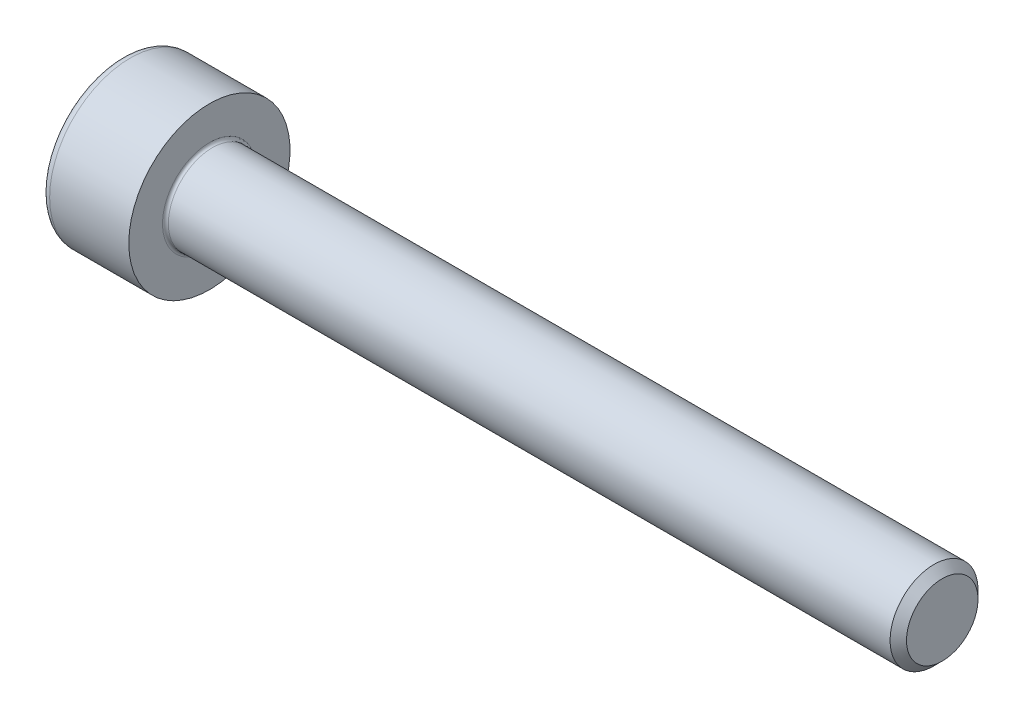
SolidWorks part; units mm, degrees
ref_plane "Plane1" through (0, 0, 0) normal (0, 0, 1) x (1, 0, 0)
ref_plane "Plane2" through (0, 0, 0) normal (0, 1, 0) x (1, 0, 0)
ref_plane "Plane3" through (0, 0, 0) normal (1, 0, 0) x (0, 0, -1)
sketch "BodySke" plane through (0, 0, 0) normal (0, 0, 1) x (1, 0, 0)
  line L0 (0, 0) -> (0, 2.75)
  line L1 (0, 2.75) -> (3, 2.75)
  line L2 (3, 2.75) -> (3, 1.5)
  line L3 (3, 1.5) -> (27.7195, 1.5)
  line L4 (28, 1.2195) -> (28, 0)
  line L5 (28, 0) -> (0, 0)
  line L6 (-31.75, 0) -> (127, 0) construction
  line L8 (28, 1.2195) -> (27.7195, 1.5)
  line L10 (28, -1.2195) -> (27.7195, -1.5) construction
  line L11 (3.5, 9.525) -> (3.5, 3.175) construction
  line L12 (10, 9.525) -> (10, 3.175) construction
  line L13 (-32, 9.525) -> (-32, 3.175) construction
  dimension "Diameter" = 3
  dimension "Head_ht" = 3
  dimension "Length" = 25
  dimension "Body_ch_ang" = 45
  dimension "Head_dia" = 5.5
  dimension "Minor_dia" = 2.439
  dimension "Advance" = 0.5
  dimension "Thread_nom" = 18
  dimension "Thread_length" = 60
revolve "Base-Revolve" add sketch "BodySke"
cosmetic thread "ThreadCosmetic" [suppressed]
fillet "Fillet1" radius 0.1 1 edges at (3, 0, 1.5)
fillet "Fillet2" radius 0.3 1 edges at (0, 0, 2.75)
sketch "Sketch2" plane through (0, 0, 0) normal (0, 0, 1) x (1, 0, 0)
  line L0 (0, 1.26) -> (1.3, 1.26)
  line L1 (1.3, 1.26) -> (2.0275, 0)
  line L2 (-31.75, 0) -> (127, 0) construction
  line L3 (2.0275, 0) -> (0, 0)
  line L4 (0, 0) -> (0, 1.26)
  line L6 (0, 0) -> (47.625, 0) construction
  dimension "D1" = 1.26
  dimension "D2" = 60
  dimension "Depth" = 1.3
revolve "Hex-PreBroach" cut sketch "Sketch2" angle 360 about L6
sketch "Sketch3" plane through (0, 0, 0) normal (-1, 0, 0) x (0, 0.5, 0.866)
  line L0 (0.7275, 1.26) -> (-0.7275, 1.26)
  line L1 (-0.7275, 1.26) -> (-1.4549, 0)
  line L2 (0.7275, 1.26) -> (1.4549, 0)
  line L3 (0.7275, -1.26) -> (1.4549, 0)
  line L4 (0.7275, -1.26) -> (-0.7275, -1.26)
  line L5 (-0.7275, -1.26) -> (-1.4549, 0)
  dimension "D1" = 1.26
  dimension "D2" = 1.26
  dimension "Hex_size" = 2.52
extrude "Hex" cut sketch "Sketch3" against normal blind 1.3
sketch "ThdSchSke" plane through (0, 0, 0) normal (0, 0, 1) x (1, 0, 0)
  line L0 (10, -1.2195) -> (9.8036, -1.5)
  line L1 (10, -1.2195) -> (10.1964, -1.5)
  line L2 (10.1964, -1.5) -> (10.1964, -1.875)
  line L3 (-3.175, 0) -> (5.1513, 0) construction
  line L4 (0, 2.45) -> (0, -2.45) construction
  line L5 (10.1964, -1.875) -> (9.8036, -1.875)
  line L6 (9.8036, -1.875) -> (9.8036, -1.5)
  dimension "Thread_minor" = 2.439
  dimension "Diameter" = 3
  dimension "Start" = 10
  dimension "SideAngle" = 55
  dimension "VeeAngle" = 70
  dimension "Overcut" = 3.75
revolve "ThreadSchematic" [suppressed] cut sketch "ThdSchSke" angle 360 about L3
pattern_linear "ThdSchPat" [suppressed]
equation "\"D2@Sketch3\" = \"Hex_size@Sketch3\" / 2"
equation "\"D1@Sketch3\" = \"Hex_size@Sketch3\" / 2"
equation "\"D1@Sketch2\" = \"Hex_size@Sketch3\" / 2"
equation "\"Thread_minor@ThreadCosmetic\"  =  \"Minor_dia@BodySke\""
equation "\"Depth@Sketch2\" =  \"Key_eng@Hex\""
equation "\"Thread_length@ThreadCosmetic\" = ((sgn( (\"Length@BodySke\" - \"Advance@BodySke\" * 3.0) - \"Thread_nom@BodySke\" )-1)*( (\"Length@BodySke\" - \"Advance@BodySke\" * 3.0) - \"Thread_nom@BodySke\" ))/-2+ \"Thread_nom@BodySke\""
equation "\"Thread_minor@ThdSchSke\" = \"Minor_dia@BodySke\""
equation "\"Diameter@ThdSchSke\" = \"Diameter@BodySke\""
equation "\"Overcut@ThdSchSke\" = \"Diameter@BodySke\" * 1.25"
equation "\"Start@ThdSchSke\" = \"Head_ht@BodySke\" + \"Length@BodySke\" - \"Thread_length@ThreadCosmetic\"  '---Non-countersunk---"
equation "\"Num_threads@ThdSchPat\" = int( \"Thread_length@ThreadCosmetic\" / \"Advance@BodySke\" + 0.999 )  + 1"
equation "\"Advance@ThdSchPat\" = \"Thread_length@ThreadCosmetic\" /  (\"Num_threads@ThdSchPat\" - 1) 'relax it"
equation "\"Num_threads@ThdSchPat\" = \"Num_threads@ThdSchPat\" - sgn( \"Num_threads@ThdSchPat\" - 1) '---chamfered tips only---"
